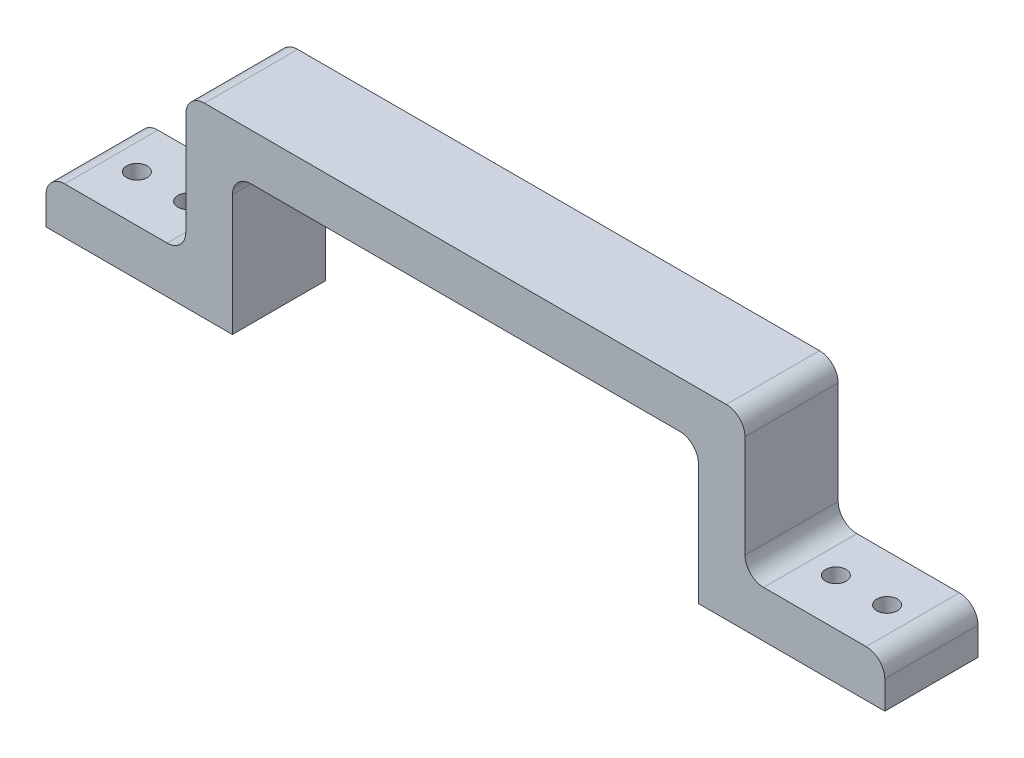
SolidWorks part; units mm, degrees
ref_plane "前视基准面" through (0, 0, 0) normal (0, 0, 1) x (1, 0, 0)
ref_plane "上视基准面" through (0, 0, 0) normal (0, 1, 0) x (1, 0, 0)
ref_plane "右视基准面" through (0, 0, 0) normal (1, 0, 0) x (0, 0, -1)
sketch "草图1" plane through (0, 0, 0) normal (0, 0, 1) x (1, 0, 0)
  line L1 (-46, 30) -> (46, 30)
  line L2 (50, 26) -> (50, 0)
  line L3 (50, 0) -> (90, 0)
  line L5 (-56, 40) -> (56, 40)
  line L6 (60, 36) -> (60, 14)
  line L7 (64, 10) -> (86, 10)
  line L8 (90, 6) -> (90, 0)
  line L9 (-90, 6) -> (-90, 0)
  line L10 (-64, 10) -> (-86, 10)
  line L11 (-60, 36) -> (-60, 14)
  line L12 (-50, 0) -> (-90, 0)
  line L13 (-50, 26) -> (-50, 0)
  arc A0 (60, 14) -> (64, 10) centre (64, 14) ccw
  arc A1 (86, 10) -> (90, 6) centre (86, 6) cw
  arc A2 (50, 26) -> (46, 30) centre (46, 26) ccw
  arc A3 (56, 40) -> (60, 36) centre (56, 36) cw
  arc A4 (-56, 40) -> (-60, 36) centre (-56, 36) ccw
  arc A5 (-50, 26) -> (-46, 30) centre (-46, 26) cw
  arc A6 (-86, 10) -> (-90, 6) centre (-86, 6) ccw
  arc A7 (-60, 14) -> (-64, 10) centre (-64, 14) cw
  dimension "D1" = 4
extrude "凸台-拉伸1" add sketch "草图1" along normal blind 20
sketch "草图2" plane through (0, 10, 0) normal (0, 1, 0) x (1, 0, 0)
  circle A0 centre (-80.5, -10) radius 2.2
  circle A1 centre (-69.5, -10) radius 2.2
  circle A2 centre (69.5, -10) radius 2.2
  circle A3 centre (80.5, -10) radius 2.2
extrude "切除-拉伸1" cut sketch "草图2" against normal blind 20
